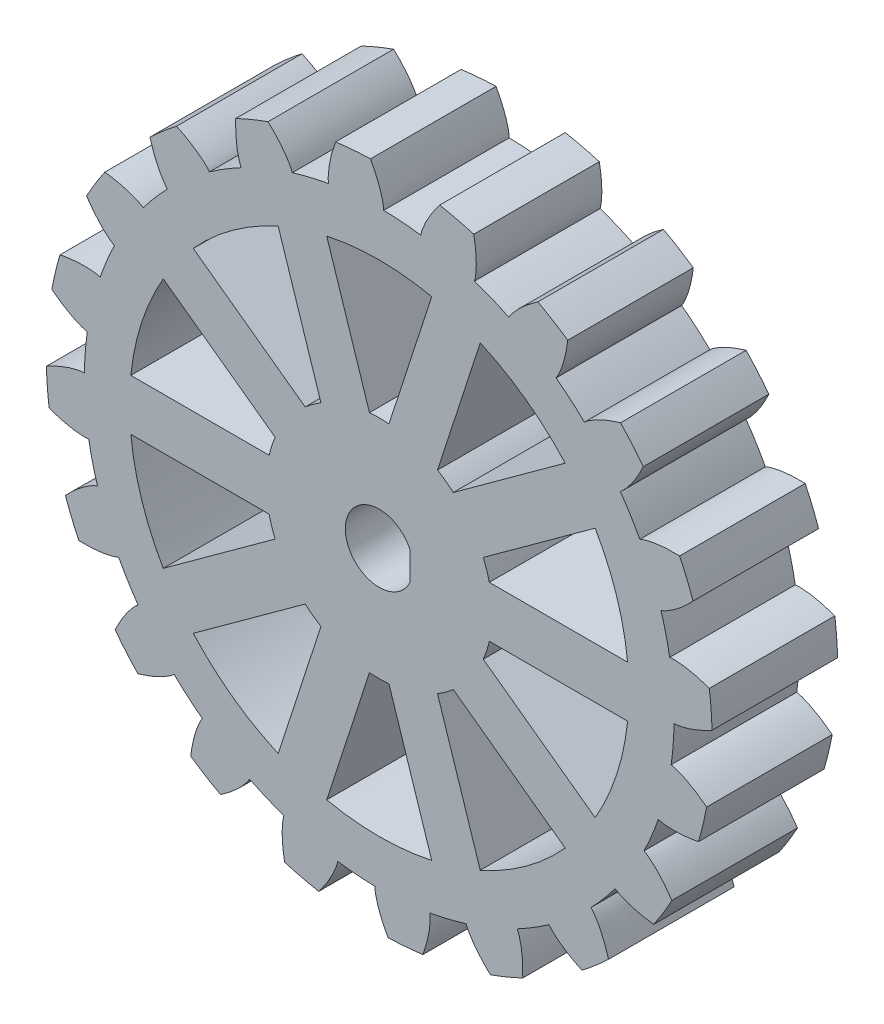
SolidWorks part; units mm, degrees
ref_plane "Front Plane" through (0, 0, 0) normal (0, 0, 1) x (1, 0, 0)
ref_plane "Top Plane" through (0, 0, 0) normal (0, 1, 0) x (1, 0, 0)
ref_plane "Right Plane" through (0, 0, 0) normal (1, 0, 0) x (0, 0, -1)
sketch "Sketch6" plane through (0, 0, 0) normal (0, 0, 1) x (1, 0, 0)
  line L0 (87.6899, 36.827) -> (87.6899, 90.4407) construction
  line L1 (87.6899, 61.8261) -> (62.7181, 61.8261) construction
  line L2 (87.6899, 61.8261) -> (56.3004, 50.4013) construction
  line L3 (79.6554, 58.9018) -> (87.6899, 61.8261) construction
  line L4 (77.8074, 58.1386) -> (87.3788, 62.5771) construction
  line L5 (76.0304, 57.2208) -> (86.9259, 63.45) construction
  line L6 (74.338, 56.1551) -> (86.3097, 64.4252) construction
  line L7 (81.5622, 59.5052) -> (87.8859, 61.2139) construction
  line L8 (83.5134, 59.9442) -> (87.9914, 60.7533) construction
  line L9 (85.4949, 60.2157) -> (88.0342, 60.454) construction
  line L10 (87.4923, 60.3177) -> (88.0428, 60.3223) construction
  line L11 (88.0428, 60.3223) -> (88.0425, 60.3158) construction
  line L12 (88.0425, 60.3158) -> (88.0425, 60.3094) construction
  line L13 (87.6899, 36.827) -> (85.2614, 67.5128) construction
  line L14 (111.173, 36.827) -> (112.6899, 36.827) construction
  line L15 (112.6899, 36.827) -> (114.2068, 36.827) construction
  circle A0 centre (87.6899, 36.827) radius 26.5169 construction
  circle A1 centre (87.6899, 36.827) radius 25 construction
  circle A2 centre (87.6899, 36.827) radius 23.4915 construction
  arc A3 (79.6554, 58.9018) -> (77.8074, 58.1386) centre (87.6899, 36.827) ccw construction
  arc A4 (77.8074, 58.1386) -> (76.0304, 57.2208) centre (87.6899, 36.827) ccw construction
  arc A5 (76.0304, 57.2208) -> (74.338, 56.1551) centre (87.6899, 36.827) ccw construction
  arc A6 (79.6554, 58.9018) -> (81.5622, 59.5052) centre (87.6899, 36.827) cw construction
  arc A7 (81.5622, 59.5052) -> (83.5134, 59.9442) centre (87.6899, 36.827) cw construction
  arc A8 (83.5134, 59.9442) -> (85.4949, 60.2157) centre (87.6899, 36.827) cw construction
  arc A9 (85.4949, 60.2157) -> (87.4923, 60.3177) centre (87.6899, 36.827) cw construction
  circle A10 centre (87.6899, 36.827) radius 23.485 construction
  spline S0 degree 3 poles (88.0425, 60.3094) (88.0393, 60.4586) (87.9965, 60.763) (87.8787, 61.2705) (87.6796, 61.8825) (87.2187, 62.9893) (86.7132, 63.8389) (86.3097, 64.4252) knots 0 0 0 0 0.099096 0.20382 0.346132 0.526411 1 1 1 1 construction
  spline S1 degree 3 poles (83.648, 59.9616) (83.6277, 60.1095) (83.6221, 60.4168) (83.6586, 60.9366) (83.759, 61.5723) (84.04, 62.7378) (84.4056, 63.6562) (84.7119, 64.2988) knots 0 0 0 0 0.099096 0.20382 0.346132 0.526411 1 1 1 1 construction
  point P7 (79.6554, 58.9018)
  dimension "D2" = 50
  dimension "D4" = 2
  dimension "D7" = 2
  dimension "D13" = 2
  dimension "D17" = 2
  dimension "D3" = 20
  dimension "D5" = 8.5502
  dimension "D6" = 10.5505
  dimension "D8" = 12.5505
  dimension "D9" = 2
  dimension "D10" = 14.5505
  dimension "D11" = 2
  dimension "D12" = 6.5505
  dimension "D14" = 4.5505
  dimension "D15" = 2
  dimension "D16" = 2.5505
  dimension "D18" = 0.5505
  dimension "D19" = 4.525
sketch "Sketch7" plane through (0, 0, 0) normal (0, 0, 1) x (1, 0, 0)
  circle A0 centre (87.6899, 36.827) radius 23.485 construction
  circle A1 centre (87.6899, 36.827) radius 26.5169 construction
  arc A2 (88.0425, 60.3094) -> (83.648, 59.9616) centre (87.6899, 36.827) ccw construction
  arc A3 (86.9912, 63.3347) -> (84.2104, 63.1146) centre (87.6899, 36.827) ccw construction
  spline S0 degree 3 poles (-1911.6865, 35.1483) (71.5756, 40.4372) (89.8382, 52.8293) (87.8787, 61.2705) (87.6796, 61.8825) (75.5402, 91.0375) (-65.3864, 59.6539) (2084.1552, 156.0334) knots -5.410264 -5.410264 -5.410264 -5.410264 0.099096 0.20382 0.346132 0.526411 21.176223 21.176223 21.176223 21.176223 only from (88.0425, 60.3094) to (86.3097, 64.4252) construction
  spline S1 degree 3 poles (2062.4411, 349.6638) (103.0357, 42.927) (83.0512, 52.2922) (83.6586, 60.9366) (83.759, 61.5723) (91.1612, 92.2738) (235.27, 83.4481) (-1902.673, -159.4872) knots -5.410264 -5.410264 -5.410264 -5.410264 0.099096 0.20382 0.346132 0.526411 21.176223 21.176223 21.176223 21.176223 only from (83.648, 59.9616) to (84.7119, 64.2988) construction
  spline S2 degree 3 poles (88.0425, 60.3094) (88.0393, 60.4586) (87.9965, 60.763) (87.8787, 61.2705) (87.6796, 61.8825) (87.3837, 62.5931) (87.1297, 63.087) (86.9912, 63.3347) knots 0 0 0 0 0.099096 0.20382 0.346132 0.526411 0.715001 0.715001 0.715001 0.715001 construction
  spline S3 degree 3 poles (83.648, 59.9616) (83.6277, 60.1095) (83.6221, 60.4168) (83.6586, 60.9366) (83.759, 61.5723) (83.9394, 62.3206) (84.1125, 62.8482) (84.2104, 63.1146) knots 0 0 0 0 0.099096 0.20382 0.346132 0.526411 0.715001 0.715001 0.715001 0.715001 construction
sketch "Sketch11" plane through (0, 0, 0) normal (0, 0, 1) x (1, 0, 0)
  circle A0 centre (0, 0) radius 23.485
  dimension "D1" = 46.97
extrude "Boss-Extrude6" add sketch "Sketch11" along normal blind 10
sketch "Sketch12" plane through (0, 0, 10) normal (0, 0, 1) x (1, 0, 0)
  arc A2 (-0.6987, 26.5077) -> (-3.4795, 26.2876) centre (0, 0) ccw
  arc A3 (0.3526, 23.4824) -> (-4.0419, 23.1346) centre (0, 0) ccw
  spline S2 degree 3 poles (-4.0419, 23.1346) (-4.0622, 23.2824) (-4.0678, 23.5897) (-4.0313, 24.1095) (-3.9309, 24.7452) (-3.7505, 25.4935) (-3.5774, 26.0212) (-3.4795, 26.2876) knots 0 0 0 0 0.099096 0.20382 0.346132 0.526411 0.715001 0.715001 0.715001 0.715001
  spline S3 degree 3 poles (0.3526, 23.4824) (0.3494, 23.6316) (0.3066, 23.9359) (0.1887, 24.4435) (-0.0104, 25.0555) (-0.3062, 25.7661) (-0.5602, 26.26) (-0.6987, 26.5077) knots 0 0 0 0 0.099096 0.20382 0.346132 0.526411 0.715001 0.715001 0.715001 0.715001
extrude "Boss-Extrude7" add sketch "Sketch12" against normal blind 10
pattern_circular "CirPattern2" count 20 over 360 of "Boss-Extrude7"
sketch "Sketch13" plane through (0, 0, 10) normal (0, 0, 1) x (1, 0, 0)
  line L0 (2.45, 1.1347) -> (2.45, -1.1347)
  arc A0 (2.45, 1.1347) -> (2.45, -1.1347) centre (0, 0) ccw
  dimension "D1" = 5.4
  dimension "D2" = 2.45
extrude "Cut-Extrude2" cut sketch "Sketch13" against normal blind 10
sketch "Sketch14" plane through (0, 0, 0) normal (0, 0, -1) x (-1, 0, 0)
  line L1 (-7.3601, 2.8365) -> (-17.1995, 9.9851)
  line L2 (-7.6217, -2.0314) -> (-19.7838, -2.0314)
  line L4 (-7.6217, 2.0314) -> (-19.7838, 2.0314)
  line L8 (-4.972, 6.1234) -> (-14.8114, 13.2721)
  line L9 (-4.2873, 6.6209) -> (-8.0455, 18.1877)
  line L10 (-0.4232, 7.8764) -> (-4.1815, 19.4432)
  line L11 (0.4232, 7.8764) -> (4.1815, 19.4432)
  line L12 (4.2873, 6.6209) -> (8.0455, 18.1877)
  line L13 (4.972, 6.1234) -> (14.8114, 13.2721)
  line L14 (7.3601, 2.8365) -> (17.1995, 9.9851)
  line L15 (7.6217, 2.0314) -> (19.7838, 2.0314)
  line L16 (7.6217, -2.0314) -> (19.7838, -2.0314)
  line L17 (7.3601, -2.8365) -> (17.1995, -9.9851)
  line L18 (4.972, -6.1234) -> (14.8114, -13.2721)
  line L19 (4.2873, -6.6209) -> (8.0455, -18.1877)
  line L20 (0.4232, -7.8764) -> (4.1815, -19.4432)
  line L21 (-0.4232, -7.8764) -> (-4.1815, -19.4432)
  line L22 (-4.2873, -6.6209) -> (-8.0455, -18.1877)
  line L23 (-4.972, -6.1234) -> (-14.8114, -13.2721)
  line L24 (-7.3601, -2.8365) -> (-17.1995, -9.9851)
  circle A0 centre (0, 0) radius 19.8878 construction
  arc A1 (-4.1815, -19.4432) -> (4.1815, -19.4432) centre (0, 0) ccw
  circle A2 centre (0, 0) radius 22.8878 construction
  arc A3 (-0.4232, -7.8764) -> (0.4232, -7.8764) centre (0, 0) ccw
  circle A4 centre (0, 0) radius 7.8878 construction
  arc A5 (-4.972, -6.1234) -> (-4.2873, -6.6209) centre (0, 0) ccw
  arc A6 (-14.8114, -13.2721) -> (-8.0455, -18.1877) centre (0, 0) ccw
  arc A7 (4.2873, -6.6209) -> (4.972, -6.1234) centre (0, 0) ccw
  arc A8 (8.0455, -18.1877) -> (14.8114, -13.2721) centre (0, 0) ccw
  arc A9 (17.1995, -9.9851) -> (19.7838, -2.0314) centre (0, 0) ccw
  arc A10 (7.3601, -2.8365) -> (7.6217, -2.0314) centre (0, 0) ccw
  arc A11 (7.6217, 2.0314) -> (7.3601, 2.8365) centre (0, 0) ccw
  arc A12 (19.7838, 2.0314) -> (17.1995, 9.9851) centre (0, 0) ccw
  arc A13 (4.972, 6.1234) -> (4.2873, 6.6209) centre (0, 0) ccw
  arc A14 (14.8114, 13.2721) -> (8.0455, 18.1877) centre (0, 0) ccw
  arc A15 (0.4232, 7.8764) -> (-0.4232, 7.8764) centre (0, 0) ccw
  arc A16 (4.1815, 19.4432) -> (-4.1815, 19.4432) centre (0, 0) ccw
  arc A17 (-4.2873, 6.6209) -> (-4.972, 6.1234) centre (0, 0) ccw
  arc A18 (-8.0455, 18.1877) -> (-14.8114, 13.2721) centre (0, 0) ccw
  arc A19 (-7.3601, 2.8365) -> (-7.6217, 2.0314) centre (0, 0) ccw
  arc A20 (-17.1995, 9.9851) -> (-19.7838, 2.0314) centre (0, 0) ccw
  arc A21 (-19.7838, -2.0314) -> (-17.1995, -9.9851) centre (0, 0) ccw
  arc A22 (-7.6217, -2.0314) -> (-7.3601, -2.8365) centre (0, 0) ccw
  point P8 (-13.8878, 0)
  point P56 (0, 0)
  dimension "D1" = 3
  dimension "D2" = 12
  dimension "D3" = 10
extrude "Cut-Extrude3" cut sketch "Sketch14" against normal through all
sketch "Sketch16" plane through (0, 0, 0) normal (0, 0, -1) x (-1, 0, 0)
  line L0 (-2.45, -1.1347) -> (-2.45, 1.1347) construction
  line L1 (-2.45, -1.1347) -> (-2.45, 1.1347)
  arc A0 (-2.45, -1.1347) -> (-2.45, 1.1347) centre (0, 0) ccw construction
  arc A1 (-2.45, -1.1347) -> (-2.45, 1.1347) centre (0, 0) ccw
  circle A2 centre (0, 0) radius 9
  dimension "D1" = 18
extrude "Boss-Extrude9" add sketch "Sketch16" along normal blind 10 and the other way up to surface
sketch "Sketch17" plane through (2.45, 0, 0) normal (-1, 0, 0) x (0, 0, 1)
  line L0 (-10, 1.1347) -> (-10, -1.1347) construction
  circle A0 centre (-5, 0) radius 1
  dimension "D1" = 2
  dimension "D2" = 5
extrude "Cut-Extrude4" cut sketch "Sketch17" against normal blind 20
